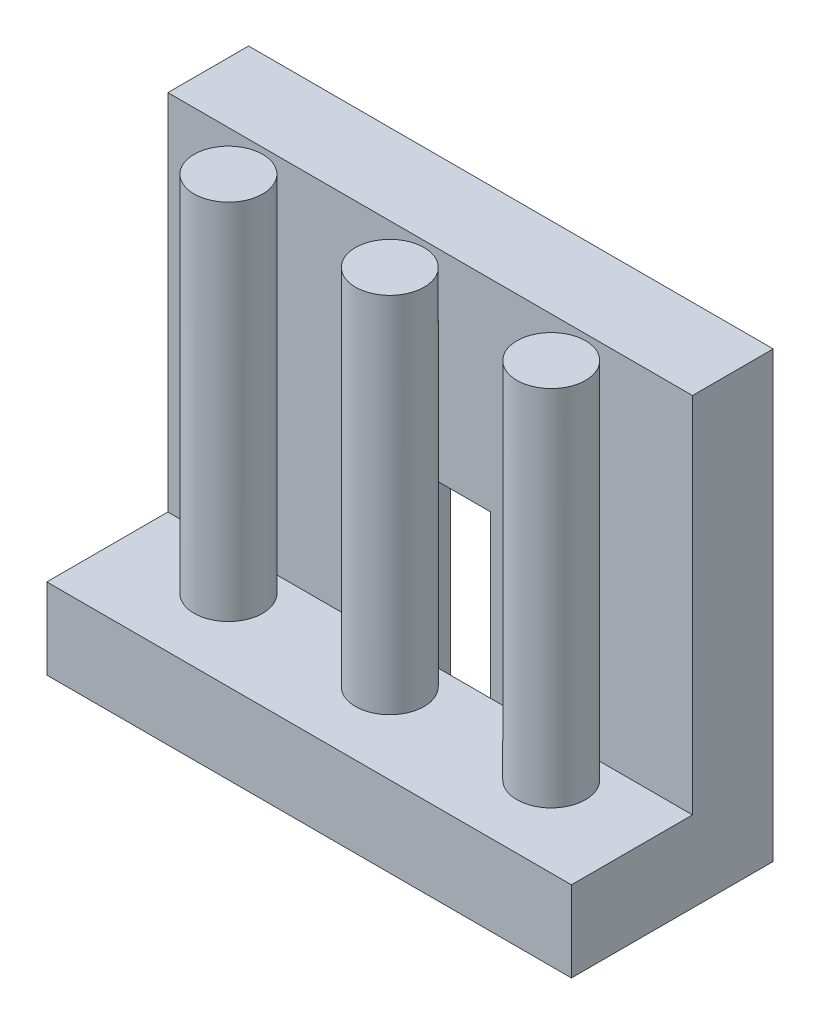
SolidWorks part; units mm, degrees
ref_plane "Front Plane" through (0, 0, 0) normal (0, 0, 1) x (1, 0, 0)
ref_plane "Top Plane" through (0, 0, 0) normal (0, 1, 0) x (1, 0, 0)
ref_plane "Right Plane" through (0, 0, 0) normal (1, 0, 0) x (0, 0, -1)
sketch "Sketch1" plane through (0, 0, 0) normal (0, 1, 0) x (1, 0, 0)
  line L1 (0, 0) -> (13, 0)
  line L2 (0, 0) -> (0, 5)
  line L3 (0, 5) -> (13, 5)
  line L4 (13, 0) -> (13, 5)
  dimension "D1" = 13
  dimension "D2" = 5
extrude "Boss-Extrude1" add sketch "Sketch1" along normal blind 11
sketch "Sketch2" plane through (0, 11, 0) normal (0, 1, 0) x (1, 0, 0)
  line L0 (13, 5) -> (0, 5) construction
  line L1 (13, 3) -> (0, 3)
  line L2 (13, 3) -> (13, 0)
  line L3 (13, 0) -> (0, 0)
  line L4 (0, 3) -> (0, 0)
  line L5 (13, 0) -> (13, 5) construction
  point P6 (0, 0)
  point P8 (13, 0)
  dimension "D1" = 2
extrude "Cut-Extrude1" cut sketch "Sketch2" against normal blind 9
sketch "Sketch3" plane through (0, 0, -5) normal (0, 0, -1) x (-1, 0, 0)
  line L0 (-13, 11) -> (-13, 0) construction
  line L1 (-5, 6) -> (-8, 6)
  line L2 (-5, 6) -> (-5, 0)
  line L3 (-5, 0) -> (-8, 0)
  line L4 (-8, 6) -> (-8, 0)
  line L5 (0, 11) -> (0, 0) construction
  line L7 (-13, 0) -> (0, 0) construction
  point P8 (-8, 0)
  point P10 (-5.3011, -0.7361)
  dimension "D1" = 5
  dimension "D2" = 5
  dimension "D3" = 6
extrude "Cut-Extrude2" cut sketch "Sketch3" against normal blind 2
sketch "Sketch4" plane through (0, 2, 0) normal (0, 1, 0) x (1, 0, 0)
  line L0 (0, 0) -> (13, 0) construction
  line L1 (13, 3) -> (0, 3) construction
  line L2 (8, 3) -> (5, 3) construction
  line L3 (13, 0) -> (13, 3) construction
  line L4 (0, 3) -> (0, 0) construction
  circle A0 centre (10.5, 2) radius 0.85
  circle A1 centre (6.5, 2) radius 0.85
  circle A2 centre (2.5, 2) radius 0.85
  dimension "D1" = 2
  dimension "D2" = 1
  dimension "D3" = 1
  dimension "D4" = 1
  dimension "D5" = 1.7
  dimension "D6" = 1.7
  dimension "D7" = 1.7
  dimension "D8" = 4
  dimension "D9" = 4
  dimension "D10" = 2.5
  dimension "D11" = 2.5
extrude "Boss-Extrude3" add sketch "Sketch4" along normal blind 9
